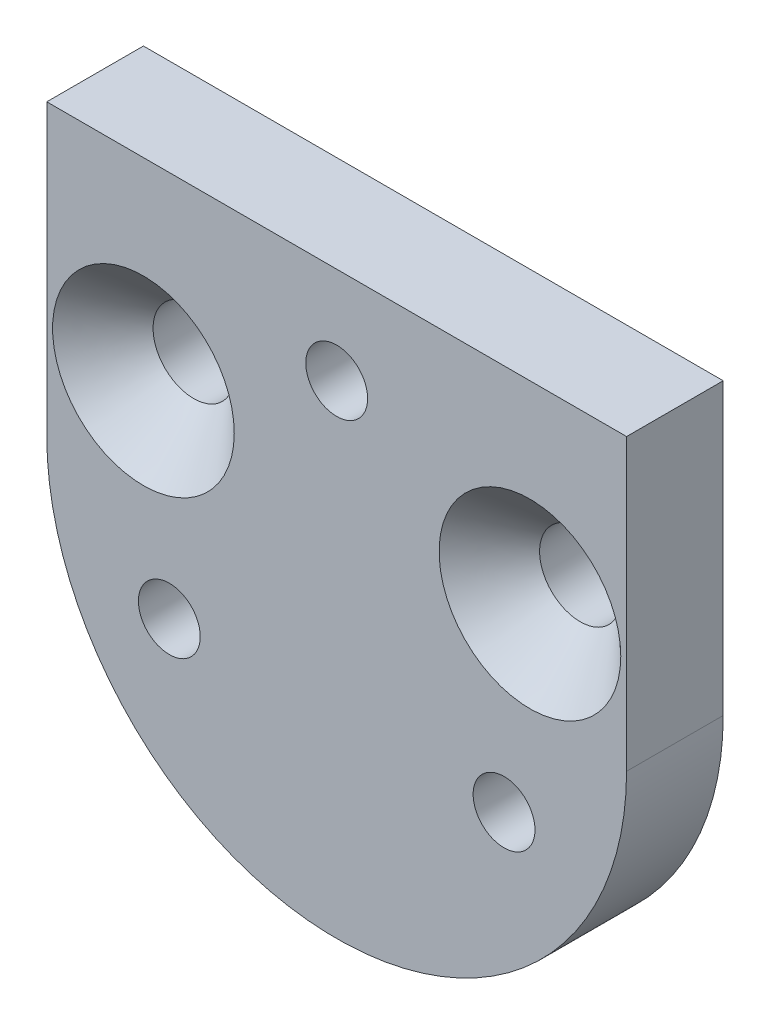
SolidWorks part; units mm, degrees
ref_plane "Спереди" through (0, 0, 0) normal (0, 0, 1) x (1, 0, 0)
ref_plane "Сверху" through (0, 0, 0) normal (0, 1, 0) x (1, 0, 0)
ref_plane "Справа" through (0, 0, 0) normal (1, 0, 0) x (0, 0, -1)
sketch "Эскиз1" plane through (0, 0, 0) normal (0, 0, 1) x (1, 0, 0)
  line L1 (-15, 15) -> (15, 15)
  line L2 (-15, 15) -> (-15, 0)
  line L4 (15, 15) -> (15, 0)
  arc A0 (-15, 0) -> (15, 0) centre (0, 0) ccw
  dimension "D3" = 30
extrude "Бобышка-Вытянуть1" add sketch "Эскиз1" along normal blind 5
sketch "Эскиз2" plane through (0, 0, 5) normal (0, 0, 1) x (1, 0, 0)
  circle A0 centre (0, 0) radius 10 construction
  circle A1 centre (0, 10) radius 1.6
  circle A2 centre (8.6603, -5) radius 1.6
  circle A3 centre (-8.6603, -5) radius 1.6
  point P12 (0, 0)
  dimension "D1" = 20
  dimension "D2" = 3.2
  dimension "D3" = 3
extrude "Вырез-Вытянуть1" cut sketch "Эскиз2" against normal through all
hole_wizard "Зенковка для винта с полупотайной головкой M41" positions "Трехмерный эскиз1" profile "Эскиз3" countersink size "M4" standard "ISO"
sketch3d "Трехмерный эскиз1"
  line L0 (15, 15, 5) -> (-15, 15, 5) construction
  line L1 (-15, 15, 5) -> (-15, 0, 5) construction
  line L2 (15, 0, 5) -> (15, 15, 5) construction
  point P0 (-10, 5, 5)
  point P2 (10, 5, 5)
  dimension "D1" = 20
  dimension "D2" = 10
  dimension "D3" = 5
  dimension "D4" = 5
sketch "Эскиз3" plane through (-10, 5, 5) normal (1, 0, 0) x (0, -1, 0)
  line L0 (0, 0) -> (0, 9.7618)
  line L1 (0, 9.7618) -> (2.1, 8.5)
  line L2 (2.1, 8.5) -> (2.1, 2.6)
  line L3 (2.1, 2.6) -> (4.7, 0)
  line L5 (4.7, 0) -> (0, 0)
  line L6 (-2.1, 2.6) -> (-4.7, 0) construction
  line L10 (0, 9.7618) -> (-2.1, 8.5) construction
  line L11 (0, -6.35) -> (0, 107.95) construction
  dimension "Диаметр отверстия" = 4.2
  dimension "Глубина отверстия" = 8.5
  dimension "Диаметр передней зенковки" = 9.4
  dimension "Угол передней зенковки" = 90
  dimension "Угол заточки сверла" = 118
sketch "Эскиз4" plane through (0, 0, 0) normal (0, 0, -1) x (-1, 0, 0)
  line L1 (3.2332, 10) -> (1.6166, 12.8)
  line L2 (1.6166, 12.8) -> (-1.6166, 12.8)
  line L3 (-1.6166, 12.8) -> (-3.2332, 10)
  line L4 (-3.2332, 10) -> (-1.6166, 7.2)
  line L5 (-1.6166, 7.2) -> (1.6166, 7.2)
  line L6 (1.6166, 7.2) -> (3.2332, 10)
  line L7 (11.8934, -5) -> (10.2768, -2.2)
  line L8 (10.2768, -2.2) -> (7.0437, -2.2)
  line L9 (7.0437, -2.2) -> (5.4271, -5)
  line L10 (5.4271, -5) -> (7.0437, -7.8)
  line L11 (7.0437, -7.8) -> (10.2768, -7.8)
  line L12 (10.2768, -7.8) -> (11.8934, -5)
  line L13 (-5.4271, -5) -> (-7.0437, -2.2)
  line L14 (-7.0437, -2.2) -> (-10.2768, -2.2)
  line L15 (-10.2768, -2.2) -> (-11.8934, -5)
  line L16 (-11.8934, -5) -> (-10.2768, -7.8)
  line L17 (-10.2768, -7.8) -> (-7.0437, -7.8)
  line L18 (-7.0437, -7.8) -> (-5.4271, -5)
  circle A0 centre (0, 10) radius 2.8 construction
  circle A1 centre (8.6603, -5) radius 2.8 construction
  circle A2 centre (-8.6603, -5) radius 2.8 construction
  dimension "D1" = 5.6
extrude "Вырез-Вытянуть2" cut sketch "Эскиз4" against normal blind 2.6
